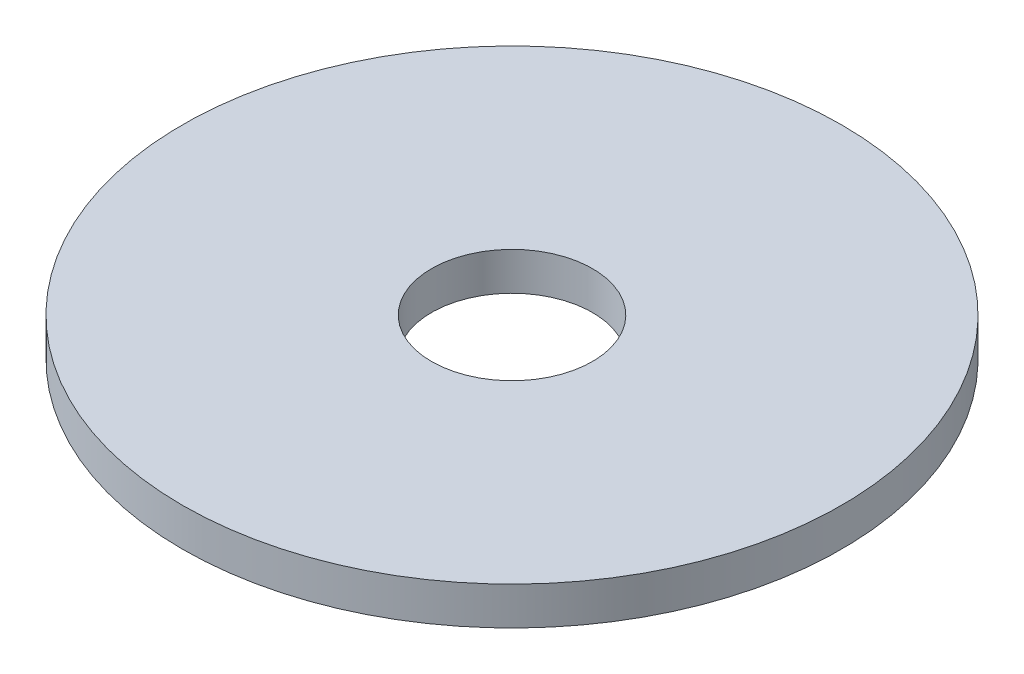
SolidWorks part; units mm, degrees
ref_plane "Front Plane" through (0, 0, 0) normal (0, 0, 1) x (1, 0, 0)
ref_plane "Top Plane" through (0, 0, 0) normal (0, 1, 0) x (1, 0, 0)
ref_plane "Right Plane" through (0, 0, 0) normal (1, 0, 0) x (0, 0, -1)
sketch "Sketch1" plane through (0, 0, 0) normal (0, 1, 0) x (1, 0, 0)
  circle A0 centre (0, 0) radius 26
  circle A1 centre (0, 0) radius 6.35
  dimension "D1" = 52
  dimension "D2" = 12.7
extrude "Boss-Extrude1" add sketch "Sketch1" along normal blind 3
